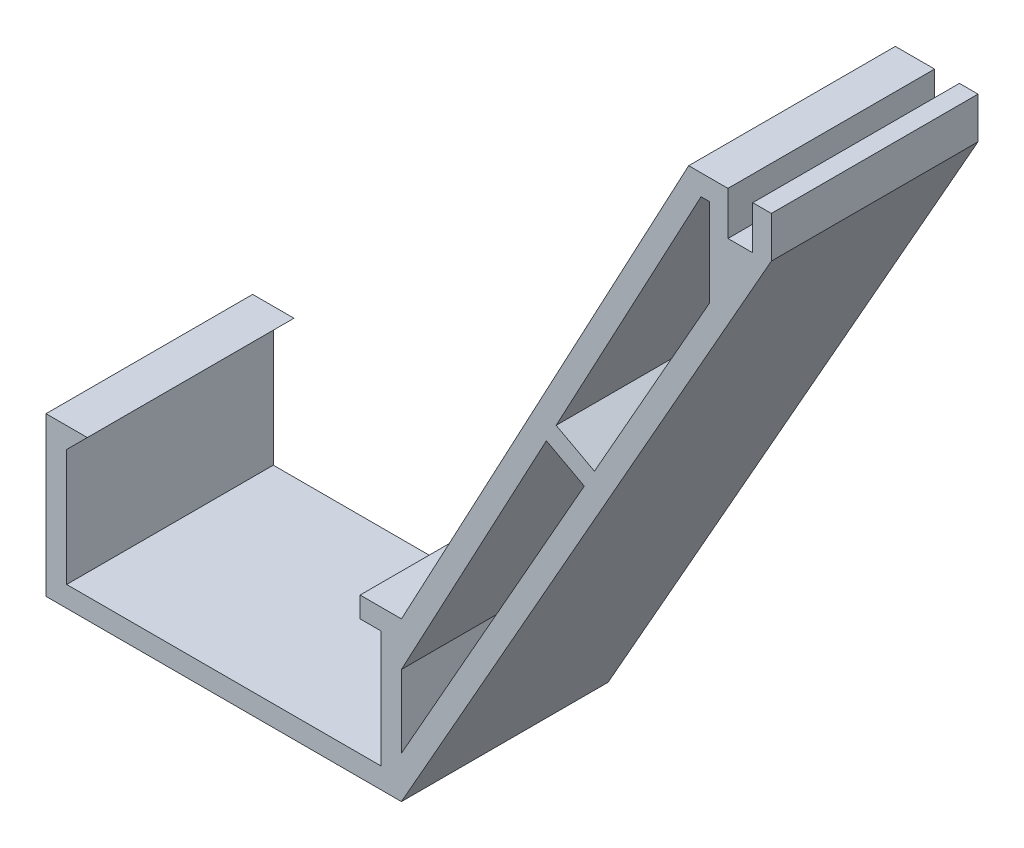
SolidWorks part; units mm, degrees
ref_plane "Front Plane" through (0, 0, 0) normal (0, 0, 1) x (1, 0, 0)
ref_plane "Top Plane" through (0, 0, 0) normal (0, 1, 0) x (1, 0, 0)
ref_plane "Right Plane" through (0, 0, 0) normal (1, 0, 0) x (0, 0, -1)
sketch "Sketch1" plane through (0, 0, 0) normal (0, 0, 1) x (1, 0, 0)
  line L0 (-15, 4.085) -> (-15, 15) construction
  line L1 (15, -15) -> (-15, -15) construction
  line L2 (15, -15) -> (15, -4.085) construction
  line L3 (15, 15) -> (-15, 15) construction
  line L4 (-15, -15) -> (-15, -4.085) construction
  line L5 (15, -15) -> (-15, 15) construction
  line L6 (15, 15) -> (-15, -15) construction
  line L7 (-15, 4.085) -> (-10, 4.085) construction
  line L9 (-15, -4.085) -> (-10, -4.085) construction
  line L10 (-10, 4.085) -> (-10, -4.085) construction
  line L11 (15, -4.085) -> (10, -4.085) construction
  line L13 (15, 4.085) -> (10, 4.085) construction
  line L14 (10, -4.085) -> (10, 4.085) construction
  line L15 (15, 4.085) -> (15, 15) construction
  line L16 (-15.2, -15.2) -> (-15.2, -3.885)
  line L25 (15.2, -3.885) -> (13.2, -3.885)
  line L26 (15.2, -15.2) -> (15.2, -3.885)
  line L27 (15.2, -15.2) -> (-15.2, -15.2)
  line L28 (-10.2, 3.885) -> (-10.2, -3.885) construction
  line L29 (-15.2, 3.885) -> (-10.2, 3.885) construction
  line L30 (-15.2, 3.885) -> (-15.2, 15.2) construction
  line L31 (15.2, 15.2) -> (-15.2, 15.2) construction
  line L32 (15.2, 3.885) -> (15.2, 15.2) construction
  line L33 (15.2, 3.885) -> (10.2, 3.885) construction
  line L34 (10.2, -3.885) -> (10.2, 3.885) construction
  line L35 (17.2, -1.885) -> (13.2, -1.885)
  line L36 (17.2, -17.2) -> (17.2, -1.885)
  line L37 (17.2, -17.2) -> (-17.2, -17.2)
  line L38 (-17.2, -17.2) -> (-17.2, -1.885)
  line L39 (-17.2, -1.885) -> (-13.2, -1.885)
  line L40 (13.2, -1.885) -> (13.2, -3.885)
  line L41 (-15.2, -3.885) -> (-13.2, -1.885)
  line L42 (-17.2, -1.885) -> (-10.2, -1.885) construction
  line L43 (-15.2, -3.885) -> (-10.2, -3.885) construction
  line L44 (17.2, -1.885) -> (10.2, -1.885) construction
  line L45 (15.2, -3.885) -> (10.2, -3.885) construction
  point P0 (0, 0)
  point P14 (-10, 0)
  point P15 (10, 0)
  dimension "D1" = 30
  dimension "D2" = 30
  dimension "D3" = 8.17
  dimension "D4" = 5
  dimension "D7" = 2
  dimension "D8" = 225
  dimension "D5" = 0.2
  dimension "D6" = 2
extrude "Boss-Extrude1" add sketch "Sketch1" along normal blind 20
sketch "Sketch2" plane through (0, 0, 0) normal (0, 0, -1) x (-1, 0, 0)
  line L0 (-15, -4.085) -> (-45, 50) construction
  line L1 (-45, 50) -> (-48.8, 50) construction
  line L2 (-51, 50) -> (-51, 86) construction
  line L3 (-51, 86) -> (-45, 86) construction
  line L4 (-45, 86) -> (-45, 84) construction
  line L5 (-45, 84) -> (-49, 84) construction
  line L6 (-49, 84) -> (-49, 52) construction
  line L7 (-49, 52) -> (-45, 52) construction
  line L8 (-45, 52) -> (-45, 50) construction
  line L9 (-51, 50) -> (-51, 46) construction
  line L10 (-51, 46) -> (-49, 46) construction
  line L11 (-49, 46) -> (-49, 50) construction
  line L12 (-45, 50) -> (-17.2, -1.885)
  line L13 (-45, 50) -> (-48.8, 50)
  line L14 (-53, 50) -> (-53, 46)
  line L15 (-53, 46) -> (-17.2, -17.2)
  line L16 (-17.2, -1.885) -> (-17.2, -6.1198)
  line L17 (-46.1974, 48) -> (-32.171, 21.8216)
  line L19 (-47, 39.4657) -> (-35.8798, 19.8344)
  line L22 (-46.1974, 48) -> (-51, 48) construction
  line L23 (-51, 46.5271) -> (-19.2, -9.6114) construction
  line L24 (-51, 48) -> (-51, 46.5271) construction
  line L25 (-46.1974, 48) -> (-47, 48)
  line L26 (-47, 48) -> (-47, 39.4657)
  line L27 (-46.1974, 48) -> (-19.2, -2.387) construction
  line L28 (-19.2, -2.387) -> (-19.2, -9.6114) construction
  line L29 (-17.2, -13.1422) -> (-17.2, -17.2)
  line L30 (-17.2, -1.885) -> (-17.2, -17.2) construction
  line L31 (-51.2, 50) -> (-51.2, 45.8)
  line L32 (-51.2, 45.8) -> (-48.8, 45.8)
  line L33 (-48.8, 45.8) -> (-48.8, 50)
  line L34 (-51.2, 50) -> (-53, 50)
  line L35 (-45, 50) -> (-53, 50) construction
  line L36 (-31.6987, 20.9401) -> (-35.3867, 18.9641) construction
  line L37 (-32.171, 21.8216) -> (-35.8798, 19.8344)
  line L38 (-31.2264, 20.0587) -> (-34.8937, 18.0937)
  line L39 (-32.171, 21.8216) -> (-35.859, 19.8455) construction
  line L40 (-31.2264, 20.0587) -> (-34.9145, 18.0826) construction
  line L41 (-34.8937, 18.0937) -> (-17.2, -13.1422)
  line L42 (-31.2264, 20.0587) -> (-17.2, -6.1198)
  line L43 (-31.6987, 20.9401) -> (-35.3867, 18.9641) construction
  point P40 (-36.8879, 10.836)
  point P42 (0, 0)
  dimension "D1" = 30
  dimension "D2" = 35
  dimension "D3" = 32
  dimension "D4" = 2
  dimension "D5" = 2
  dimension "D6" = 2
  dimension "D7" = 4
  dimension "D8" = 4
  dimension "D9" = 2
  dimension "D11" = 2
  dimension "D10" = 2
  dimension "D12" = 0.2
  dimension "D13" = 1
  dimension "D14" = 1
extrude "Boss-Extrude2" add sketch "Sketch2" against normal up to surface (20 mm away) up to face at (1.2, -7.6359, 20)
